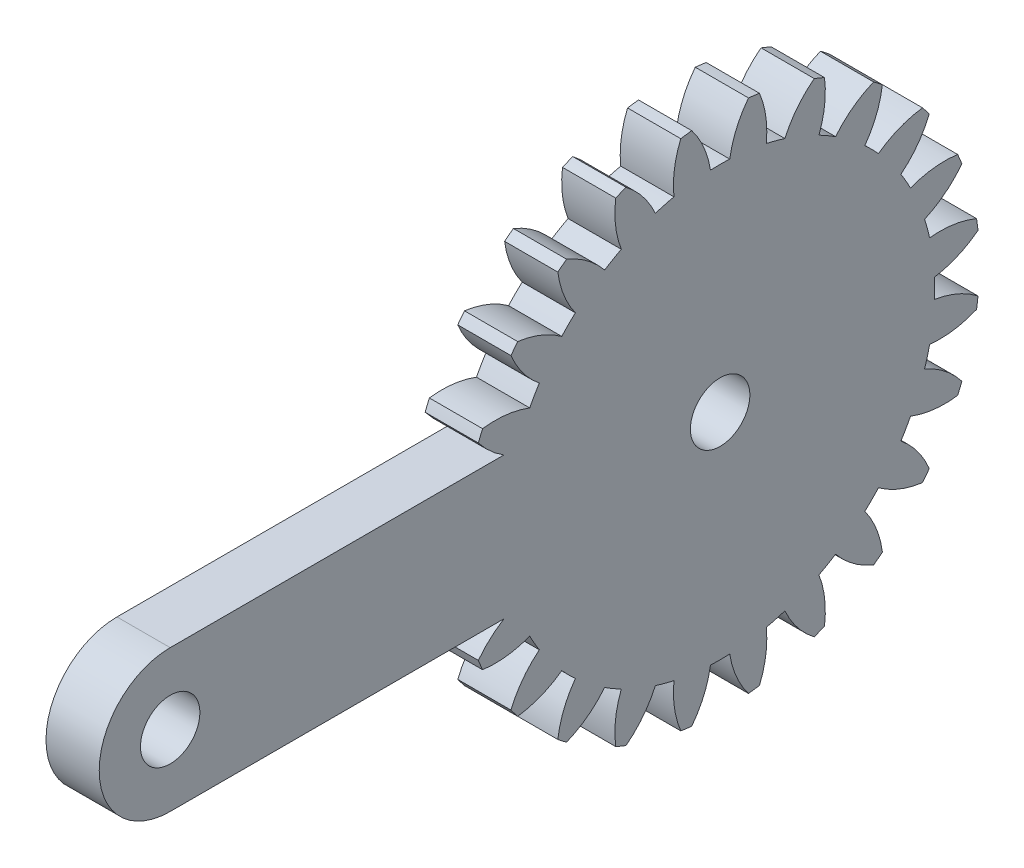
SolidWorks part; units mm, degrees
ref_plane "Front Plane" through (0, 0, 0) normal (0, 0, 1) x (1, 0, 0)
ref_plane "Top Plane" through (0, 0, 0) normal (0, 1, 0) x (1, 0, 0)
ref_plane "Right Plane" through (0, 0, 0) normal (1, 0, 0) x (0, 0, -1)
ref_plane "Plane1" through (3, 0, 0) normal (1, 0, 0) x (0, 0, -1)
sketch "Sketch1" plane through (3, 0, 0) normal (1, 0, 0) x (0, 0, -1)
  circle A0 centre (0, 0) radius 1.675
  arc A1 (-14.5373, 1.5991) -> (-12.0806, 0.5427) centre (-11.2423, 5.8773) ccw
  arc A2 (-12.0806, 0.5427) -> (-12.0806, -0.5427) centre (0, 0) ccw
  arc A3 (-12.0806, -0.5427) -> (-14.5373, -1.5991) centre (-11.2423, -5.8773) ccw
  arc A4 (-14.5373, -1.5991) -> (-14.4558, -2.2179) centre (0, 0) ccw
  arc A5 (-14.4558, -2.2179) -> (-11.8094, -2.6025) centre (-12.3803, 2.7673) ccw
  arc A6 (-11.8094, -2.6025) -> (-11.5285, -3.6509) centre (0, 0) ccw
  arc A7 (-11.5285, -3.6509) -> (-13.6281, -5.3071) centre (-9.3381, -8.5867) ccw
  arc A8 (-13.6281, -5.3071) -> (-13.3892, -5.8838) centre (0, 0) ccw
  arc A9 (-13.3892, -5.8838) -> (-10.7334, -5.5703) centre (-12.6747, -0.5313) ccw
  arc A10 (-10.7334, -5.5703) -> (-10.1907, -6.5103) centre (0, 0) ccw
  arc A11 (-10.1907, -6.5103) -> (-11.7901, -8.6535) centre (-6.7975, -10.711) ccw
  arc A12 (-11.7901, -8.6535) -> (-11.4102, -9.1487) centre (0, 0) ccw
  arc A13 (-11.4102, -9.1487) -> (-8.926, -8.1585) centre (-12.1053, -3.7936) ccw
  arc A14 (-8.926, -8.1585) -> (-8.1585, -8.926) centre (0, 0) ccw
  arc A15 (-8.1585, -8.926) -> (-9.1487, -11.4102) centre (-3.7936, -12.1053) ccw
  arc A16 (-9.1487, -11.4102) -> (-8.6535, -11.7901) centre (0, 0) ccw
  arc A17 (-8.6535, -11.7901) -> (-6.5103, -10.1907) centre (-10.711, -6.7975) ccw
  arc A18 (-6.5103, -10.1907) -> (-5.5703, -10.7334) centre (0, 0) ccw
  arc A19 (-5.5703, -10.7334) -> (-5.8838, -13.3892) centre (-0.5313, -12.6747) ccw
  arc A20 (-5.8838, -13.3892) -> (-5.3071, -13.6281) centre (0, 0) ccw
  arc A21 (-5.3071, -13.6281) -> (-3.6509, -11.5285) centre (-8.5867, -9.3381) ccw
  arc A22 (-3.6509, -11.5285) -> (-2.6025, -11.8094) centre (0, 0) ccw
  arc A23 (-2.6025, -11.8094) -> (-2.2179, -14.4558) centre (2.7673, -12.3803) ccw
  arc A24 (-2.2179, -14.4558) -> (-1.5991, -14.5373) centre (0, 0) ccw
  arc A25 (-1.5991, -14.5373) -> (-0.5427, -12.0806) centre (-5.8773, -11.2423) ccw
  arc A26 (-0.5427, -12.0806) -> (0.5427, -12.0806) centre (0, 0) ccw
  arc A27 (0.5427, -12.0806) -> (1.5991, -14.5373) centre (5.8773, -11.2423) ccw
  arc A28 (1.5991, -14.5373) -> (2.2179, -14.4558) centre (0, 0) ccw
  arc A29 (2.2179, -14.4558) -> (2.6025, -11.8094) centre (-2.7673, -12.3803) ccw
  arc A30 (2.6025, -11.8094) -> (3.6509, -11.5285) centre (0, 0) ccw
  arc A31 (3.6509, -11.5285) -> (5.3071, -13.6281) centre (8.5867, -9.3381) ccw
  arc A32 (5.3071, -13.6281) -> (5.8838, -13.3892) centre (0, 0) ccw
  arc A33 (5.8838, -13.3892) -> (5.5703, -10.7334) centre (0.5313, -12.6747) ccw
  arc A34 (5.5703, -10.7334) -> (6.5103, -10.1907) centre (0, 0) ccw
  arc A35 (6.5103, -10.1907) -> (8.6535, -11.7901) centre (10.711, -6.7975) ccw
  arc A36 (8.6535, -11.7901) -> (9.1487, -11.4102) centre (0, 0) ccw
  arc A37 (9.1487, -11.4102) -> (8.1585, -8.926) centre (3.7936, -12.1053) ccw
  arc A38 (8.1585, -8.926) -> (8.926, -8.1585) centre (0, 0) ccw
  arc A39 (8.926, -8.1585) -> (11.4102, -9.1487) centre (12.1053, -3.7936) ccw
  arc A40 (11.4102, -9.1487) -> (11.7901, -8.6535) centre (0, 0) ccw
  arc A41 (11.7901, -8.6535) -> (10.1907, -6.5103) centre (6.7975, -10.711) ccw
  arc A42 (10.1907, -6.5103) -> (10.7334, -5.5703) centre (0, 0) ccw
  arc A43 (10.7334, -5.5703) -> (13.3892, -5.8838) centre (12.6747, -0.5313) ccw
  arc A44 (13.3892, -5.8838) -> (13.6281, -5.3071) centre (0, 0) ccw
  arc A45 (13.6281, -5.3071) -> (11.5285, -3.6509) centre (9.3381, -8.5867) ccw
  arc A46 (11.5285, -3.6509) -> (11.8094, -2.6025) centre (0, 0) ccw
  arc A47 (11.8094, -2.6025) -> (14.4558, -2.2179) centre (12.3803, 2.7673) ccw
  arc A48 (14.4558, -2.2179) -> (14.5373, -1.5991) centre (0, 0) ccw
  arc A49 (14.5373, -1.5991) -> (12.0806, -0.5427) centre (11.2423, -5.8773) ccw
  arc A50 (12.0806, -0.5427) -> (12.0806, 0.5427) centre (0, 0) ccw
  arc A51 (12.0806, 0.5427) -> (14.5373, 1.5991) centre (11.2423, 5.8773) ccw
  arc A52 (14.5373, 1.5991) -> (14.4558, 2.2179) centre (0, 0) ccw
  arc A53 (14.4558, 2.2179) -> (11.8094, 2.6025) centre (12.3803, -2.7673) ccw
  arc A54 (11.8094, 2.6025) -> (11.5285, 3.6509) centre (0, 0) ccw
  arc A55 (11.5285, 3.6509) -> (13.6281, 5.3071) centre (9.3381, 8.5867) ccw
  arc A56 (13.6281, 5.3071) -> (13.3892, 5.8838) centre (0, 0) ccw
  arc A57 (13.3892, 5.8838) -> (10.7334, 5.5703) centre (12.6747, 0.5313) ccw
  arc A58 (10.7334, 5.5703) -> (10.1907, 6.5103) centre (0, 0) ccw
  arc A59 (10.1907, 6.5103) -> (11.7901, 8.6535) centre (6.7975, 10.711) ccw
  arc A60 (11.7901, 8.6535) -> (11.4102, 9.1487) centre (0, 0) ccw
  arc A61 (11.4102, 9.1487) -> (8.926, 8.1585) centre (12.1053, 3.7936) ccw
  arc A62 (8.926, 8.1585) -> (8.1585, 8.926) centre (0, 0) ccw
  arc A63 (8.1585, 8.926) -> (9.1487, 11.4102) centre (3.7936, 12.1053) ccw
  arc A64 (9.1487, 11.4102) -> (8.6535, 11.7901) centre (0, 0) ccw
  arc A65 (8.6535, 11.7901) -> (6.5103, 10.1907) centre (10.711, 6.7975) ccw
  arc A66 (6.5103, 10.1907) -> (5.5703, 10.7334) centre (0, 0) ccw
  arc A67 (5.5703, 10.7334) -> (5.8838, 13.3892) centre (0.5313, 12.6747) ccw
  arc A68 (5.8838, 13.3892) -> (5.3071, 13.6281) centre (0, 0) ccw
  arc A69 (5.3071, 13.6281) -> (3.6509, 11.5285) centre (8.5867, 9.3381) ccw
  arc A70 (3.6509, 11.5285) -> (2.6025, 11.8094) centre (0, 0) ccw
  arc A71 (2.6025, 11.8094) -> (2.2179, 14.4558) centre (-2.7673, 12.3803) ccw
  arc A72 (2.2179, 14.4558) -> (1.5991, 14.5373) centre (0, 0) ccw
  arc A73 (1.5991, 14.5373) -> (0.5427, 12.0806) centre (5.8773, 11.2423) ccw
  arc A74 (0.5427, 12.0806) -> (-0.5427, 12.0806) centre (0, 0) ccw
  arc A75 (-0.5427, 12.0806) -> (-1.5991, 14.5373) centre (-5.8773, 11.2423) ccw
  arc A76 (-1.5991, 14.5373) -> (-2.2179, 14.4558) centre (0, 0) ccw
  arc A77 (-2.2179, 14.4558) -> (-2.6025, 11.8094) centre (2.7673, 12.3803) ccw
  arc A78 (-2.6025, 11.8094) -> (-3.6509, 11.5285) centre (0, 0) ccw
  arc A79 (-3.6509, 11.5285) -> (-5.3071, 13.6281) centre (-8.5867, 9.3381) ccw
  arc A80 (-5.3071, 13.6281) -> (-5.8838, 13.3892) centre (0, 0) ccw
  arc A81 (-5.8838, 13.3892) -> (-5.5703, 10.7334) centre (-0.5313, 12.6747) ccw
  arc A82 (-5.5703, 10.7334) -> (-6.5103, 10.1907) centre (0, 0) ccw
  arc A83 (-6.5103, 10.1907) -> (-8.6535, 11.7901) centre (-10.711, 6.7975) ccw
  arc A84 (-8.6535, 11.7901) -> (-9.1487, 11.4102) centre (0, 0) ccw
  arc A85 (-9.1487, 11.4102) -> (-8.1585, 8.926) centre (-3.7936, 12.1053) ccw
  arc A86 (-8.1585, 8.926) -> (-8.926, 8.1585) centre (0, 0) ccw
  arc A87 (-8.926, 8.1585) -> (-11.4102, 9.1487) centre (-12.1053, 3.7936) ccw
  arc A88 (-11.4102, 9.1487) -> (-11.7901, 8.6535) centre (0, 0) ccw
  arc A89 (-11.7901, 8.6535) -> (-10.1907, 6.5103) centre (-6.7975, 10.711) ccw
  arc A90 (-10.1907, 6.5103) -> (-10.7334, 5.5703) centre (0, 0) ccw
  arc A91 (-10.7334, 5.5703) -> (-13.3892, 5.8838) centre (-12.6747, 0.5313) ccw
  arc A92 (-13.3892, 5.8838) -> (-13.6281, 5.3071) centre (0, 0) ccw
  arc A93 (-13.6281, 5.3071) -> (-11.5285, 3.6509) centre (-9.3381, 8.5867) ccw
  arc A94 (-11.5285, 3.6509) -> (-11.8094, 2.6025) centre (0, 0) ccw
  arc A95 (-11.8094, 2.6025) -> (-14.4558, 2.2179) centre (-12.3803, -2.7673) ccw
  arc A96 (-14.4558, 2.2179) -> (-14.5373, 1.5991) centre (0, 0) ccw
extrude "Boss-Extrude1" add sketch "Sketch1" against normal blind 3
sketch "Sketch2" plane through (3, 0, 0) normal (1, 0, 0) x (0, 0, -1)
  line L0 (0, 0) -> (-31, 0) construction
  line L1 (0, -4) -> (-31, -4)
  line L2 (0, 4) -> (-31, 4)
  arc A0 (0, -4) -> (0, 4) centre (0, 0) ccw
  arc A1 (-31, 4) -> (-31, -4) centre (-31, 0) ccw
  circle A2 centre (-31, 0) radius 1.675
  circle A3 centre (0, 0) radius 1.675 construction
  circle A4 centre (0, 0) radius 1.675
  point P3 (-15.5, 0)
  dimension "D2" = 8
  dimension "D3" = 3.35
  dimension "D1" = 31
extrude "Boss-Extrude2" add sketch "Sketch2" against normal blind 3
sketch "Sketch3" plane through (3, 0, 0) normal (1, 0, 0) x (0, 0, -1)
  line L0 (-16.9179, -4) -> (-11.412, -4)
  line L1 (-31, -4) -> (-12.188, -4) construction
  circle A0 centre (0, 0) radius 12.0927 construction
  arc A1 (-10.1907, 6.5103) -> (-10.7334, 5.5703) centre (0, 0) ccw construction
  arc A2 (-11.412, -4) -> (11.8094, -2.6025) centre (0, 0) ccw
